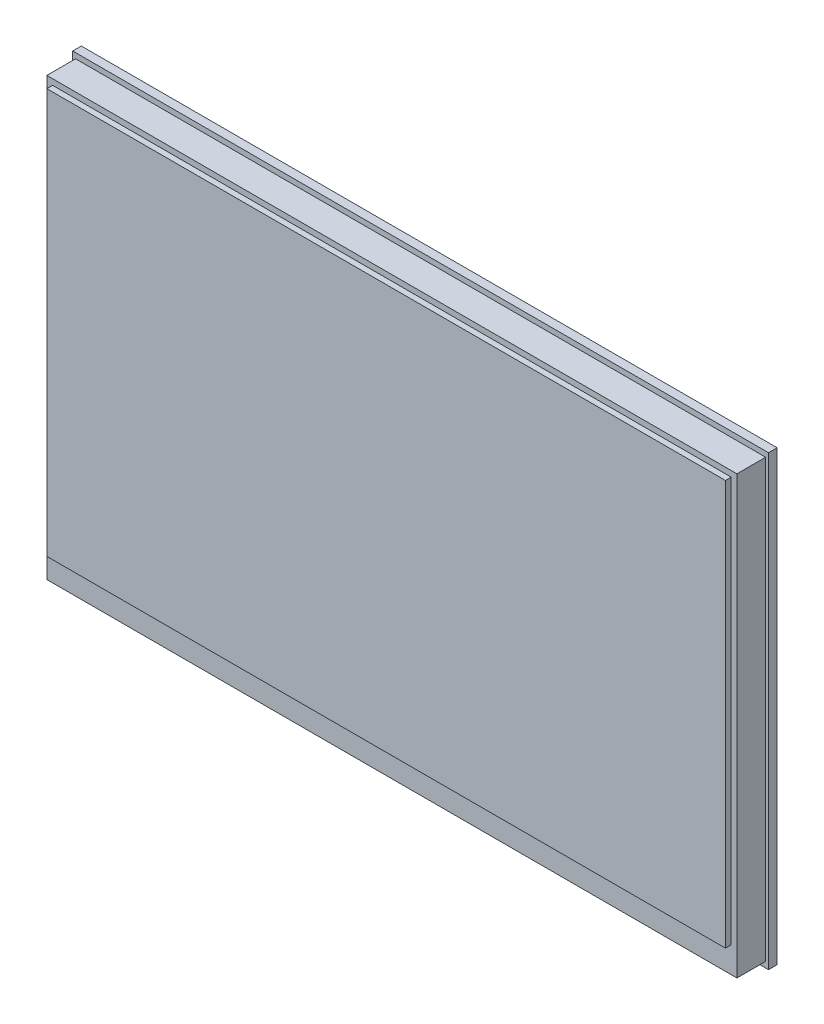
SolidWorks part; units mm, degrees
ref_plane "前视基准面" through (0, 0, 0) normal (0, 0, 1) x (1, 0, 0)
ref_plane "上视基准面" through (0, 0, 0) normal (0, 1, 0) x (1, 0, 0)
ref_plane "右视基准面" through (0, 0, 0) normal (1, 0, 0) x (0, 0, -1)
sketch "草图1" plane through (0, 0, 0) normal (0, 0, 1) x (1, 0, 0)
  line L1 (0, 0) -> (121.11, 0)
  line L2 (0, 0) -> (0, 77.93)
  line L3 (0, 77.93) -> (121.11, 77.93)
  line L4 (121.11, 0) -> (121.11, 77.93)
  dimension "D1" = 121.11
  dimension "D2" = 77.93
extrude "凸台-拉伸1" add sketch "草图1" along normal blind 1.5
hole_wizard "Ø2.0 (2) 直径孔1" positions "草图3" profile "草图2" hole size "Ø2.0" standard "GB" end condition through all
sketch "草图3" plane through (0, 0, 1.5) normal (0, 0, 1) x (1, 0, 0)
  line L0 (0, 0) -> (121.11, 0) construction
  point P0 (23.02, 74.29)
  point P2 (23.02, 5)
  point P4 (116.11, 74.29)
  point P6 (116.11, 5)
  dimension "D1" = 93.09
  dimension "D2" = 69.29
  dimension "D3" = 5
  dimension "D4" = 5
sketch "草图2" plane through (23.02, 74.29, 1.5) normal (1, 0, 0) x (0, -1, 0)
  line L0 (0, 0) -> (0, 1.5)
  line L1 (0, 1.5) -> (1, 1.5)
  line L2 (1, 1.5) -> (1, 0)
  line L5 (1, 0) -> (0, 0)
  line L11 (0, -6.35) -> (0, 107.95) construction
  dimension "通孔孔直径" = 2
  dimension "通孔孔深度" = 1.5
sketch "草图4" plane through (0, 0, 1.5) normal (0, 0, 1) x (1, 0, 0)
  line L0 (0, 77.93) -> (0, 0) construction
  line L1 (0.5, 1) -> (120.61, 1)
  line L2 (0.5, 1) -> (0.5, 77)
  line L3 (0.5, 77) -> (120.61, 77)
  line L4 (120.61, 1) -> (120.61, 77)
  line L6 (121.11, 0) -> (121.11, 77.93) construction
  dimension "D1" = 76
  dimension "D2" = 1
  dimension "D3" = 0.5
  dimension "D4" = 0.5
extrude "凸台-拉伸2" add sketch "草图4" along normal blind 5
sketch "草图5" plane through (0, 0, 6.5) normal (0, 0, 1) x (1, 0, 0)
  line L0 (0.5, 77) -> (0.5, 1) construction
  line L1 (1.5, 5.5) -> (119.61, 5.5)
  line L2 (1.5, 5.5) -> (1.5, 76)
  line L3 (1.5, 76) -> (119.61, 76)
  line L4 (119.61, 5.5) -> (119.61, 76)
  line L5 (120.61, 1) -> (120.61, 77) construction
  line L6 (120.61, 77) -> (0.5, 77) construction
  line L7 (0.5, 1) -> (120.61, 1) construction
  dimension "D1" = 1
  dimension "D2" = 1
  dimension "D3" = 1
  dimension "D4" = 4.5
extrude "凸台-拉伸3" add sketch "草图5" along normal blind 1
